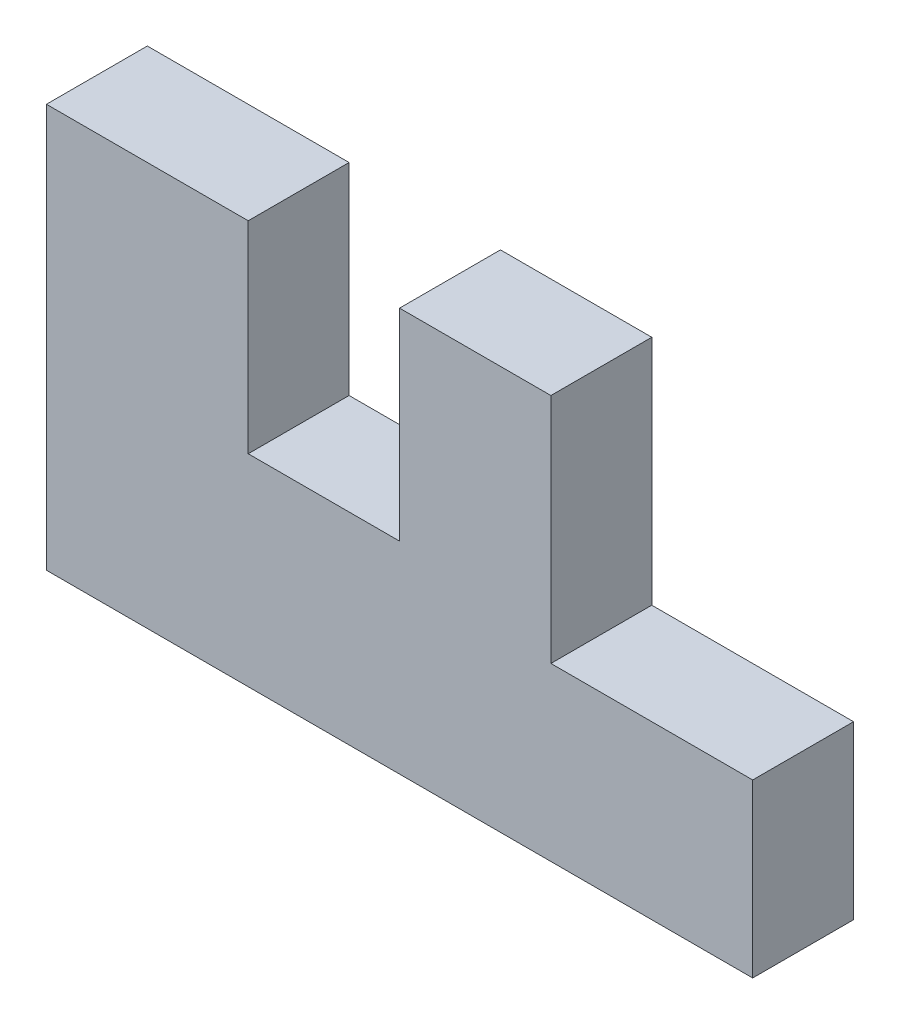
SolidWorks part; units mm, degrees
ref_plane "Front Plane" through (0, 0, 0) normal (0, 0, 1) x (1, 0, 0)
ref_plane "Top Plane" through (0, 0, 0) normal (0, 1, 0) x (1, 0, 0)
ref_plane "Right Plane" through (0, 0, 0) normal (1, 0, 0) x (0, 0, -1)
sketch "Sketch1" plane through (0, 0, 0) normal (0, 0, 1) x (1, 0, 0)
  line L0 (0, 0) -> (0, 50.8)
  line L1 (0, 0) -> (88.9, 0)
  line L2 (0, 50.8) -> (25.4, 50.8)
  line L3 (25.4, 50.8) -> (25.4, 25.4)
  line L4 (25.4, 25.4) -> (44.45, 25.4)
  line L5 (44.45, 25.4) -> (44.45, 50.8)
  line L6 (44.45, 50.8) -> (63.5, 50.8)
  line L7 (63.5, 50.8) -> (63.5, 21.59)
  line L8 (63.5, 21.59) -> (88.9, 21.59)
  line L9 (88.9, 21.59) -> (88.9, 0)
  dimension "D1" = 50.8
  dimension "D2" = 88.9
  dimension "D3" = 25.4
  dimension "D4" = 44.45
  dimension "D5" = 63.5
  dimension "D6" = 25.4
  dimension "D7" = 21.59
extrude "Boss-Extrude1" add sketch "Sketch1" along normal blind 12.7
